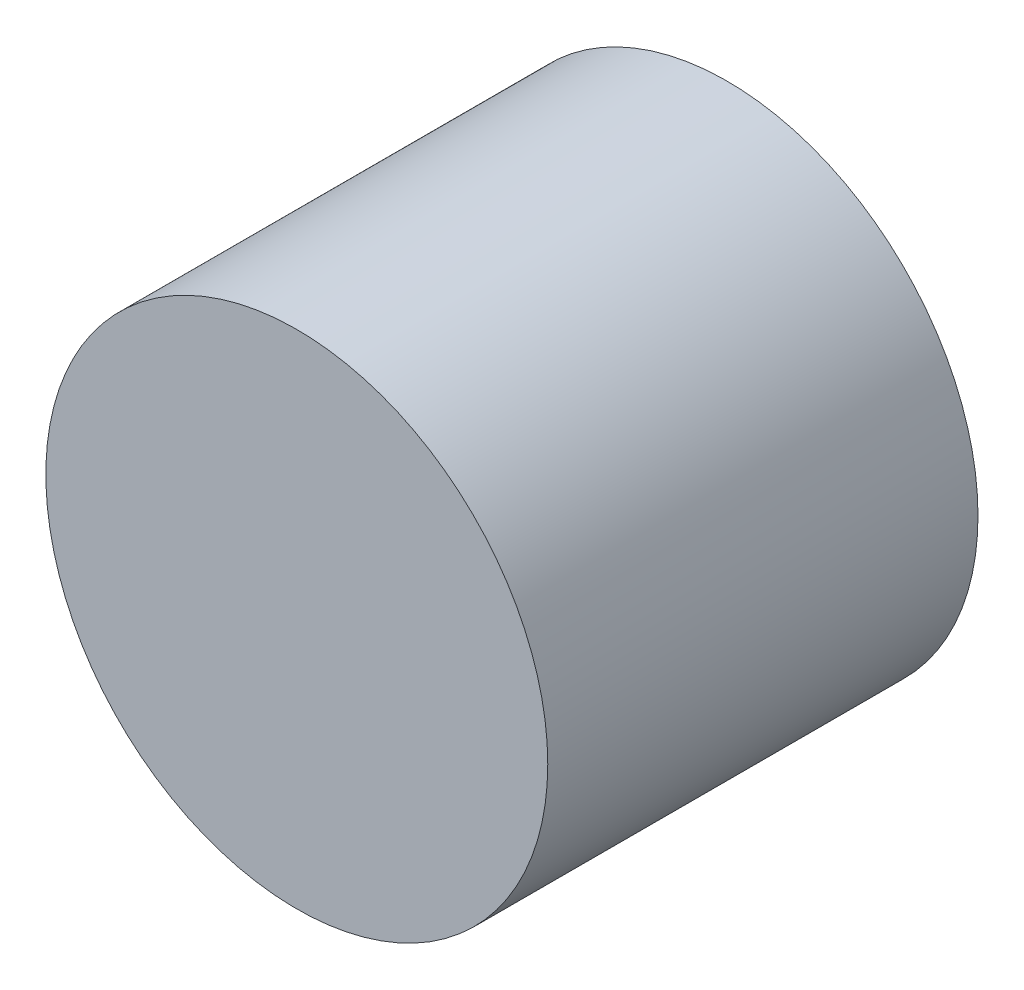
SolidWorks part; units mm, degrees
ref_plane "Płaszczyzna przednia" through (0, 0, 0) normal (0, 0, 1) x (1, 0, 0)
ref_plane "Płaszczyzna górna" through (0, 0, 0) normal (0, 1, 0) x (1, 0, 0)
ref_plane "Płaszczyzna prawa" through (0, 0, 0) normal (1, 0, 0) x (0, 0, -1)
sketch "Szkic1" plane through (0, 0, 0) normal (0, 0, 1) x (1, 0, 0)
  circle A0 centre (0, 0) radius 17.5
  dimension "D1" = 35
extrude "Dodanie-wyciągnięcie1" add sketch "Szkic1" along normal blind 30
